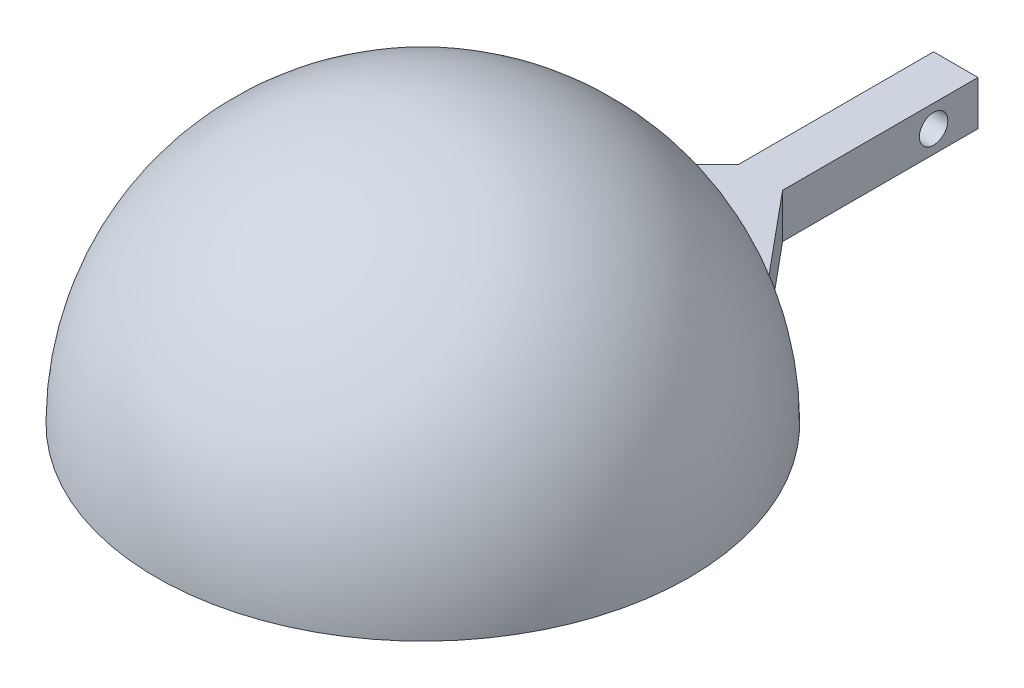
SolidWorks part; units mm, degrees
ref_plane "Front Plane" through (0, 0, 0) normal (0, 0, 1) x (1, 0, 0)
ref_plane "Top Plane" through (0, 0, 0) normal (0, 1, 0) x (1, 0, 0)
ref_plane "Right Plane" through (0, 0, 0) normal (1, 0, 0) x (0, 0, -1)
sketch "Sketch2" plane through (0, 0, 0) normal (0, 0, 1) x (1, 0, 0)
  line L0 (0, 29) -> (0, 30)
  line L1 (29, 0) -> (30, 0)
  line L2 (0, 0) -> (0, 30) construction
  circle A0 centre (0, 0) radius 30 construction
  arc A1 (0, 30) -> (30, 0) centre (0, 0) cw
  arc A2 (0, 29) -> (29, 0) centre (0, 0) cw
  dimension "D1" = 60
  dimension "D2" = 1
revolve "Revolve1" add sketch "Sketch2" angle 360 about L2
sketch "Sketch3" plane through (0, 0, 0) normal (0, -1, 0) x (1, 0, 0)
  line L0 (0, -30) -> (0, -60) construction
  line L1 (-2.039, -38) -> (6.2568, -38) construction
  line L2 (-2.5, -60) -> (2.5, -60)
  line L3 (-2.5, -60) -> (-2.5, -30)
  line L4 (-2.5, -30) -> (2.5, -30)
  line L5 (2.5, -60) -> (2.5, -30)
  line L6 (-2.5, -38) -> (2.5, -38)
  line L8 (2.5, -38) -> (12.2228, -26.308)
  line L9 (12.2228, -26.308) -> (12.2191, -26.3001)
  line L10 (-2.5, -38) -> (-14.4183, -26.308)
  line L11 (-14.4183, -26.308) -> (-13.9377, -25.4311)
  circle A0 centre (0, 0) radius 30 construction
  circle A1 centre (0, 0) radius 30 construction
  circle A2 centre (0, 0) radius 29 construction
  arc A3 (-13.9377, -25.4311) -> (12.2191, -26.3001) centre (-0.0374, -1.1251) ccw
  point P9 (0, -60)
  circle M2 centre (0, 0) radius 30
  circle M3 centre (0, 0) radius 29
  dimension "D1" = 30
  dimension "D2" = 8
  dimension "D3" = 5
extrude "Boss-Extrude1" add sketch "Sketch3" against normal blind 5 contours L10 L3 L4 M2 | L3 L6 L5 L4 | L5 L8 L4 M2 | L6 L3 L2 L5 | L11 L9 M2 M3
sketch "Sketch4" plane through (2.5, 0, 0) normal (1, 0, 0) x (0, 0, -1)
  line L0 (60, 2.5) -> (41.7869, 2.5) construction
  line L1 (60, 5) -> (60, 0) construction
  circle A0 centre (55, 2.5) radius 1.6
  dimension "D1" = 3.2
  dimension "D2" = 5
extrude "Cut-Extrude1" cut sketch "Sketch4" against normal through all
